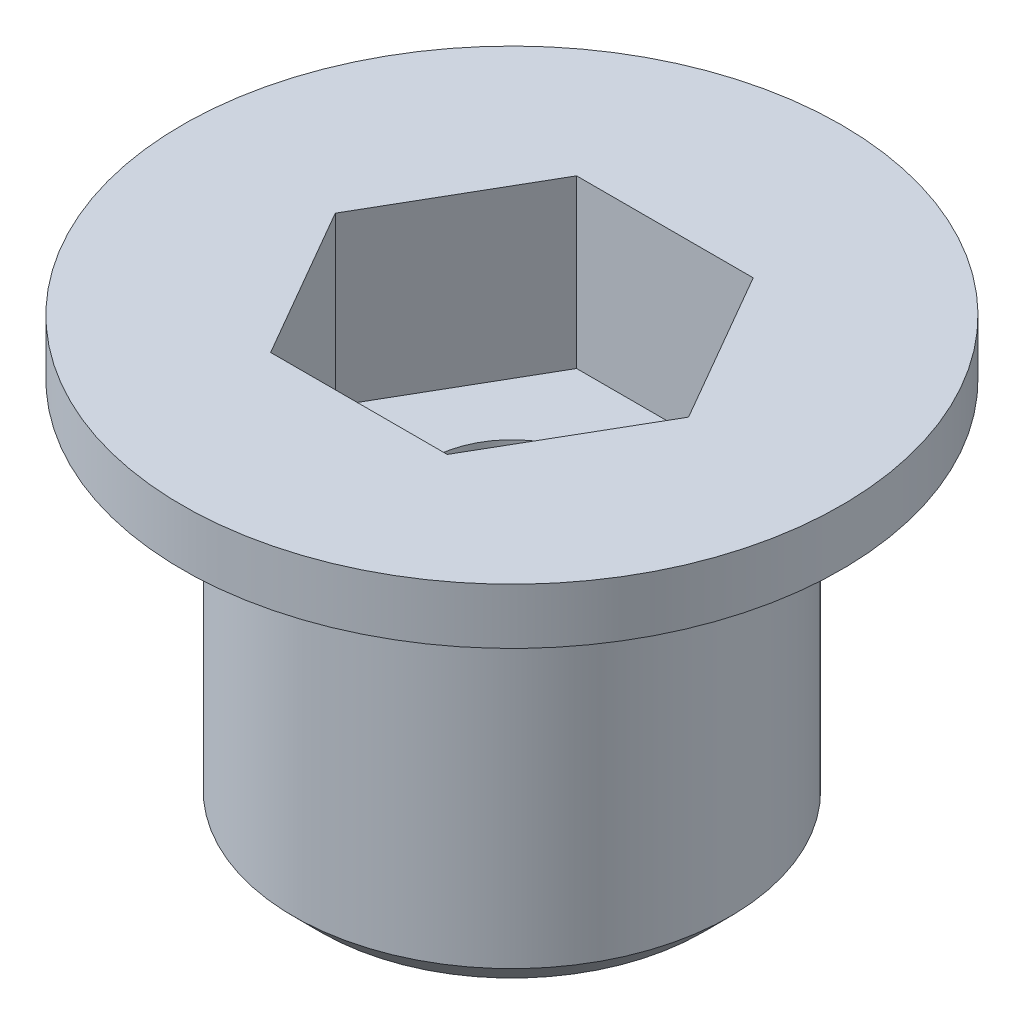
SolidWorks part; units mm, degrees
material "ABS"
ref_plane "Plan de face" through (0, 0, 0) normal (0, 0, 1) x (1, 0, 0)
ref_plane "Plan de dessus" through (0, 0, 0) normal (0, 1, 0) x (1, 0, 0)
ref_plane "Plan de droite" through (0, 0, 0) normal (1, 0, 0) x (0, 0, -1)
sketch "Esquisse1" plane through (0, 0, 0) normal (0, 0, 1) x (1, 0, 0)
  line L0 (0, 0) -> (0, 7.9) construction
  line L1 (1.5, 7.9) -> (5.925, 7.9)
  line L2 (5.925, 7.9) -> (5.925, 6.9)
  line L3 (5.925, 6.9) -> (3.925, 6.9)
  line L4 (3.925, 6.9) -> (3.925, 0)
  line L5 (3.925, 0) -> (1.5, 0)
  line L6 (1.5, 0) -> (1.5, 7.9)
  dimension "D1" = 6.9
  dimension "D2" = 1
  dimension "D3" = 7.85
  dimension "D4" = 2
  dimension "D5" = 3
revolve "Révolution1" add sketch "Esquisse1" angle 360 about L0
chamfer "Chanfrein1" distance 0.5 angle 45 2 edges at (0, 0, -3.925) (0, 6.9, -3.925)
sketch "Esquisse3" plane through (0, 7.9, 0) normal (0, 1, 0) x (1, 0, 0)
  line L1 (1.5877, 2.75) -> (-1.5877, 2.75)
  line L2 (-1.5877, 2.75) -> (-3.1754, 0)
  line L3 (-3.1754, 0) -> (-1.5877, -2.75)
  line L4 (-1.5877, -2.75) -> (1.5877, -2.75)
  line L5 (1.5877, -2.75) -> (3.1754, 0)
  line L6 (3.1754, 0) -> (1.5877, 2.75)
  circle A0 centre (0, 0) radius 2.75 construction
  dimension "D1" = 5.5
extrude "Enlèv. mat.-Extru.2" cut sketch "Esquisse3" against normal blind 3
